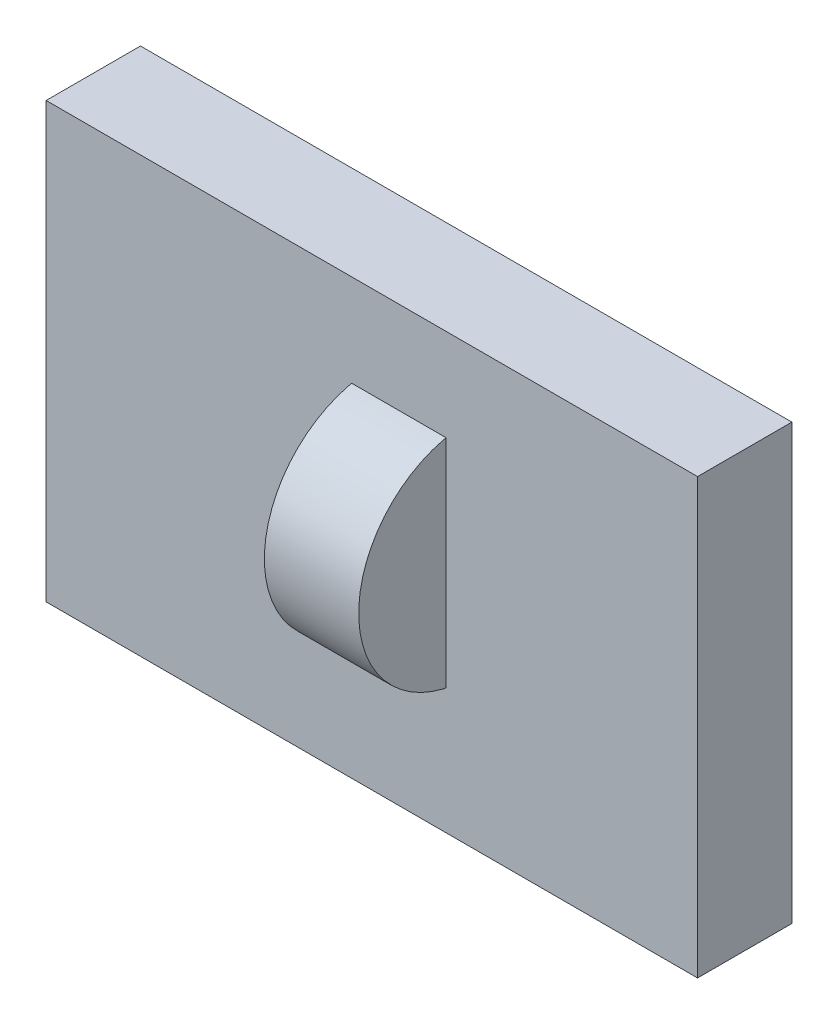
SolidWorks part; units mm, degrees
ref_plane "Спереди" through (0, 0, 0) normal (0, 0, 1) x (1, 0, 0)
ref_plane "Сверху" through (0, 0, 0) normal (0, 1, 0) x (1, 0, 0)
ref_plane "Справа" through (0, 0, 0) normal (1, 0, 0) x (0, 0, -1)
sketch "Эскиз1" plane through (0, 0, 0) normal (0, 0, 1) x (1, 0, 0)
  line L1 (-32.4073, 21.2507) -> (36.6575, 21.2507)
  line L2 (-32.4073, 21.2507) -> (-32.4073, -24.7925)
  line L3 (-32.4073, -24.7925) -> (36.6575, -24.7925)
  line L4 (36.6575, 21.2507) -> (36.6575, -24.7925)
extrude "Бобышка-Вытянуть1" add sketch "Эскиз1" against normal blind 10
sketch "Эскиз2" plane through (0, 0, 0) normal (1, 0, 0) x (0, 0, -1)
  circle A0 centre (-19.75, 0) radius 11.7674
  point P3 (-19.75, 0)
extrude "Бобышка-Вытянуть3" add sketch "Эскиз2" along normal blind 10 separate body
move or copy body "Тело-Переместить/Копировать1" bodies to move or copy 105 copy no translate (0, 0, -22.2478)
